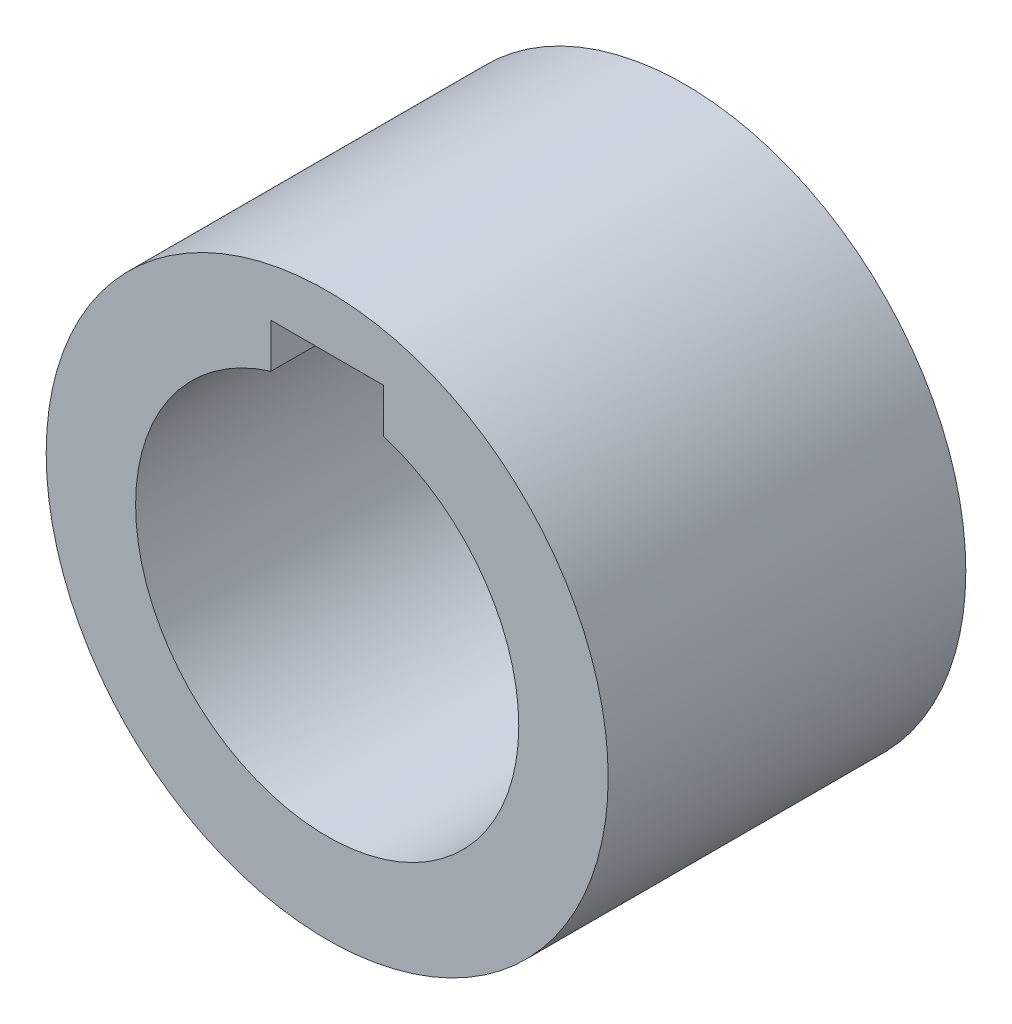
SolidWorks part; units mm, degrees
material "ASTM A36 Steel"
ref_plane "Front Plane" through (0, 0, 0) normal (0, 0, 1) x (1, 0, 0)
ref_plane "Top Plane" through (0, 0, 0) normal (0, 1, 0) x (1, 0, 0)
ref_plane "Right Plane" through (0, 0, 0) normal (1, 0, 0) x (0, 0, -1)
sketch "Sketch1" plane through (0, 0, 0) normal (0, 0, 1) x (1, 0, 0)
  circle A0 centre (0, 0) radius 55
  circle A1 centre (0, 0) radius 37.5
  dimension "D1" = 110
  dimension "D2" = 75
extrude "Boss-Extrude1" add sketch "Sketch1" along normal blind 70
sketch "Sketch2" plane through (0, 0, 70) normal (0, 0, 1) x (1, 0, 0)
  line L1 (-11, 30.5) -> (11, 30.5)
  line L2 (-11, 30.5) -> (-11, 44.5)
  line L3 (-11, 44.5) -> (11, 44.5)
  line L4 (11, 30.5) -> (11, 44.5)
  line L5 (-11, 30.5) -> (11, 44.5) construction
  line L6 (-11, 44.5) -> (11, 30.5) construction
  circle A0 centre (0, 0) radius 37.5 construction
  point P0 (0, 37.5)
  dimension "D1" = 14
  dimension "D2" = 22
extrude "Cut-Extrude1" cut sketch "Sketch2" against normal through all both and the other way through all
